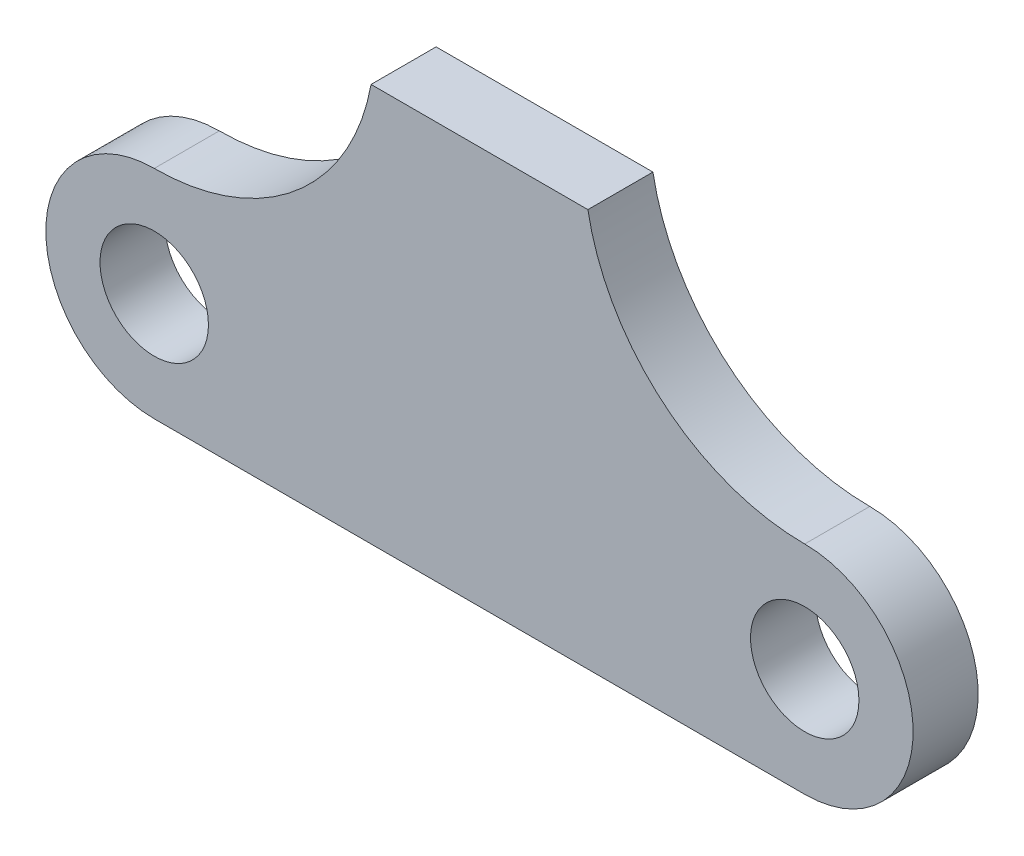
SolidWorks part; units mm, degrees
ref_plane "Front Plane" through (0, 0, 0) normal (0, 0, 1) x (1, 0, 0)
ref_plane "Top Plane" through (0, 0, 0) normal (0, 1, 0) x (1, 0, 0)
ref_plane "Right Plane" through (0, 0, 0) normal (1, 0, 0) x (0, 0, -1)
sketch "Sketch1" plane through (0, 0, 0) normal (0, 0, 1) x (1, 0, 0)
  line L0 (-15, 0) -> (15, 0) construction
  line L1 (-15, 5) -> (15, 5)
  line L2 (-15, -5) -> (15, -5)
  line L3 (-5, 13.3552) -> (5, 13.3552)
  arc A0 (-15, 5) -> (-15, -5) centre (-15, 0) ccw
  arc A1 (15, -5) -> (15, 5) centre (15, 0) ccw
  circle A2 centre (-15, 0) radius 2.5
  circle A3 centre (15, 0) radius 2.5
  arc A4 (-15, 5) -> (-5, 13.3552) centre (-15, 15.1619) ccw
  arc A5 (15, 5) -> (5, 13.3552) centre (15, 15.1619) cw
  point P2 (0, 0)
  dimension "D2" = 5
  dimension "D3" = 5
  dimension "D4" = 5
  dimension "D1" = 30
  dimension "D5" = 10
extrude "Boss-Extrude1" add sketch "Sketch1" along normal blind 3
